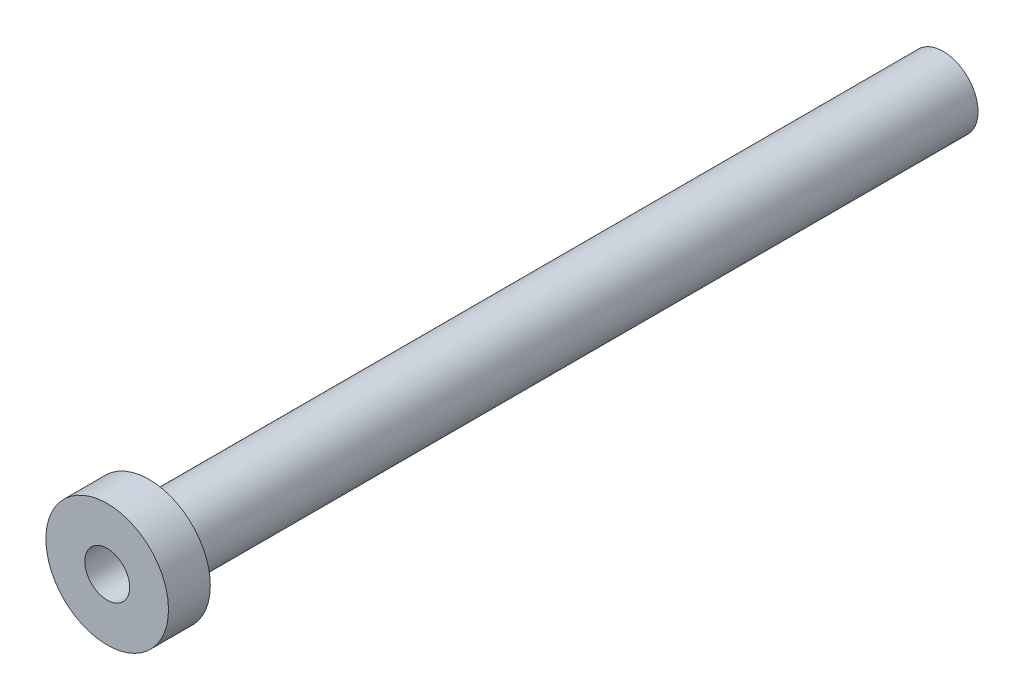
SolidWorks part; units mm, degrees
ref_plane "Front Plane" through (0, 0, 0) normal (0, 0, 1) x (1, 0, 0)
ref_plane "Top Plane" through (0, 0, 0) normal (0, 1, 0) x (1, 0, 0)
ref_plane "Right Plane" through (0, 0, 0) normal (1, 0, 0) x (0, 0, -1)
sketch "Sketch1" plane through (0, 0, 0) normal (0, 0, 1) x (1, 0, 0)
  circle A0 centre (0, 0) radius 22
  dimension "D1" = 44
extrude "Boss-Extrude1" add sketch "Sketch1" along normal blind 15
sketch "Sketch2" plane through (0, 0, 0) normal (0, 0, -1) x (-1, 0, 0)
  circle A0 centre (0, 0) radius 17.75
  circle A1 centre (0, 0) radius 12.5
  dimension "D1" = 35.5
  dimension "D2" = 25
extrude "Cut-Extrude1" cut sketch "Sketch2" against normal blind 10
sketch "Sketch3" plane through (0, 0, 15) normal (0, 0, 1) x (1, 0, 0)
  circle A0 centre (0, 0) radius 8.05
  dimension "D1" = 16.1
extrude "Cut-Extrude2" cut sketch "Sketch3" against normal through all
sketch "Sketch4" plane through (0, 0, 0) normal (0, 0, -1) x (-1, 0, 0)
  circle A0 centre (0, 0) radius 8.05 construction
  circle A1 centre (0, 0) radius 12.5
  circle A2 centre (0, 0) radius 12.5
  circle A3 centre (0, 0) radius 8.05
  dimension "D1" = 0
extrude "Boss-Extrude2" add sketch "Sketch4" along normal blind 285
